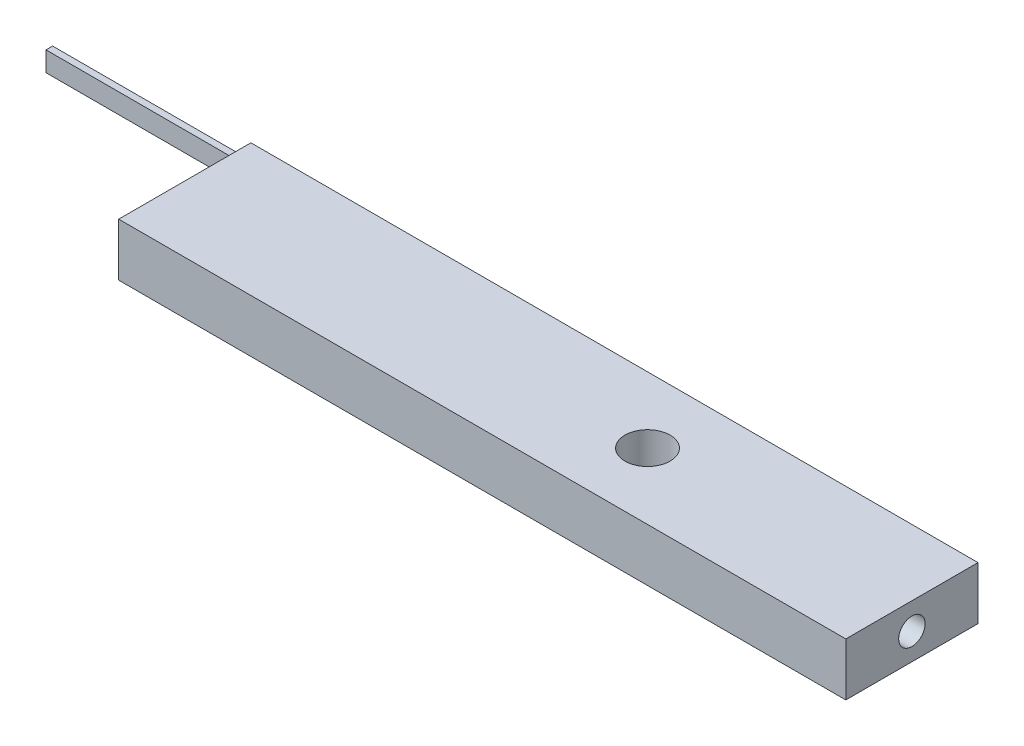
SolidWorks part; units mm, degrees
ref_plane "Front Plane" through (0, 0, 0) normal (0, 0, 1) x (1, 0, 0)
ref_plane "Top Plane" through (0, 0, 0) normal (0, 1, 0) x (1, 0, 0)
ref_plane "Right Plane" through (0, 0, 0) normal (1, 0, 0) x (0, 0, -1)
sketch "Sketch1" plane through (0, 0, 0) normal (0, 1, 0) x (1, 0, 0)
  line L1 (-431.4089, 34.934) -> (118.5911, 34.934)
  line L2 (-431.4089, 34.934) -> (-431.4089, -65.066)
  line L3 (-431.4089, -65.066) -> (118.5911, -65.066)
  line L4 (118.5911, 34.934) -> (118.5911, -65.066)
  circle A0 centre (-81.4089, -15.066) radius 17.084
  point P6 (0, 0)
  dimension "D1" = 100
  dimension "D2" = 200
  dimension "D3" = 50
  dimension "D4" = 350
extrude "Boss-Extrude1" add sketch "Sketch1" along normal blind 40
sketch "Sketch2" plane through (118.5911, 0, 0) normal (1, 0, 0) x (0, 0, -1)
  line L0 (-65.066, 40) -> (34.934, 40) construction
  line L1 (34.934, 40) -> (34.934, 0) construction
  circle A0 centre (-15.066, 20) radius 10
  dimension "D1" = 20
  dimension "D2" = 20
  dimension "D3" = 50
extrude "Cut-Extrude1" cut sketch "Sketch2" against normal blind 114
sketch "Sketch3" plane through (0, 0, -34.934) normal (0, 0, -1) x (-1, 0, 0)
  line L0 (431.4089, 40) -> (431.4089, 0) construction
  line L1 (431.4089, 28.4017) -> (581.4089, 28.4017)
  line L2 (431.4089, 28.4017) -> (431.4089, 13.4017)
  line L3 (431.4089, 13.4017) -> (581.4089, 13.4017)
  line L4 (581.4089, 28.4017) -> (581.4089, 13.4017)
  dimension "D1" = 150
  dimension "D2" = 15
extrude "Boss-Extrude2" add sketch "Sketch3" against normal blind 5 separate body
